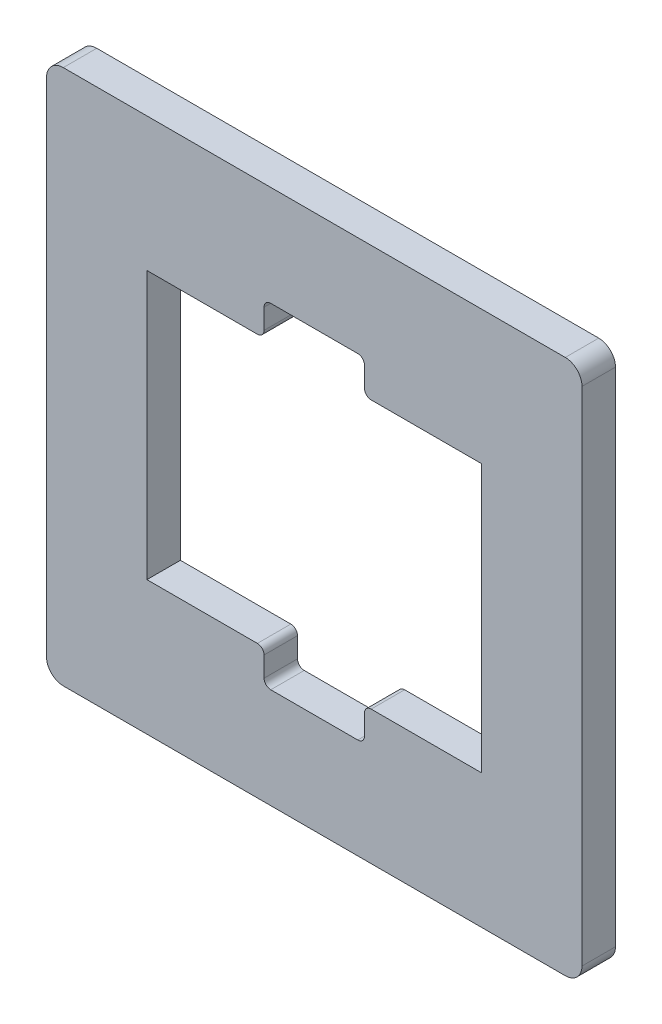
SolidWorks part; units mm, degrees
material "Silicon Rubber"
ref_plane "Front Plane" through (0, 0, 0) normal (0, 0, 1) x (1, 0, 0)
ref_plane "Top Plane" through (0, 0, 0) normal (0, 1, 0) x (1, 0, 0)
ref_plane "Right Plane" through (0, 0, 0) normal (1, 0, 0) x (0, 0, -1)
sketch "MainBodyS" plane through (0, 0, 0) normal (0, 0, 1) x (1, 0, 0)
  line L1 (-8, 8) -> (8, 8)
  line L2 (-8, 8) -> (-8, -8)
  line L3 (-8, -8) -> (8, -8)
  line L4 (8, 8) -> (8, -8)
  line L5 (-8, 8) -> (8, -8) construction
  line L6 (-8, -8) -> (8, 8) construction
  point P0 (0, 0)
  dimension "Width" = 16
  dimension "Height" = 16
extrude "MAIN BODY" add sketch "MainBodyS" against normal blind 1
sketch "MidCutS" plane through (0, 0, 0) normal (0, 0, 1) x (1, 0, 0)
  line L1 (-5, 4) -> (5, 4)
  line L2 (-5, 4) -> (-5, -4)
  line L3 (-5, -4) -> (5, -4)
  line L4 (5, 4) -> (5, -4)
  line L5 (-5, 4) -> (5, -4) construction
  line L6 (-5, -4) -> (5, 4) construction
  line L7 (-8, 8) -> (-8, -8) construction
  point P0 (0, 0)
  dimension "WidthControl" = 3
  dimension "Height" = 8
  dimension "RefWidth" = 10
extrude "MID CUT" cut sketch "MidCutS" against normal through all
sketch "GroundCutS" plane through (0, 0, 0) normal (0, 0, 1) x (1, 0, 0)
  line L0 (5, 4) -> (-5, 4) construction
  line L1 (-1.5, 5) -> (1.5, 5)
  line L2 (-1.5, 5) -> (-1.5, 4)
  line L3 (-1.5, 4) -> (1.5, 4)
  line L4 (1.5, 5) -> (1.5, 4)
  line L5 (-1.5, 5) -> (1.5, 4) construction
  line L6 (-1.5, 4) -> (1.5, 5) construction
  line L8 (-5, 4) -> (-5, -4) construction
  line L10 (0, 0) -> (0, 4.5) construction
  point P0 (0, 4.5)
  dimension "WidthControl" = 3.5
  dimension "RefWidth" = 3
  dimension "Height" = 1
extrude "GroundCut" cut sketch "GroundCutS" against normal through all
mirror "GCVM" about plane through (0, 0, 0) normal (0, 1, 0) of "GroundCut"
fillet "OUTER FILLETS" radius 0.5 4 edges at (-8, -8, -0.5) (8, -8, -0.5) (8, 8, -0.5) (-8, 8, -0.5)
fillet "GCF" radius 0.2 8 edges at (1.5, -4, -0.5) (1.5, -5, -0.5) (-1.5, -5, -0.5) (-1.5, -4, -0.5) (1.5, 4, -0.5) (1.5, 5, -0.5) (-1.5, 5, -0.5) (-1.5, 4, -0.5)
